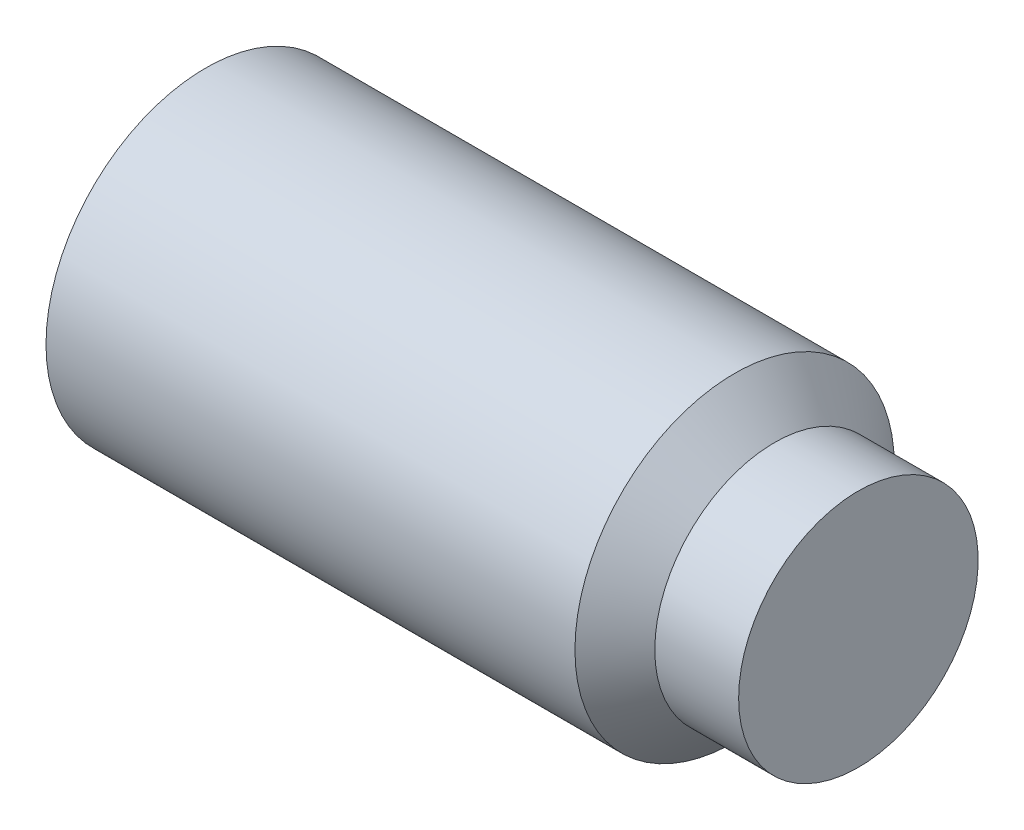
SolidWorks part; units mm, degrees
revolve "BaseBody" add sketch "BodySke" angle 360 about L5
sketch "BodySke" plane through (0, 0, 0) normal (0, 0, 1) x (1, 0, 0)
  line L0 (0, 0) -> (0, 10.352)
  line L1 (0, 10.352) -> (0.9515, 12)
  line L2 (0.9515, 12) -> (40.7, 12)
  line L3 (40.7, 12) -> (43.7, 9)
  line L4 (50, 0) -> (0, 0)
  line L5 (-12.7, 0) -> (88.9, 0) construction
  line L6 (43.7, 9) -> (50, 9)
  line L7 (50, 9) -> (50, 0)
  line L8 (0, -10.352) -> (0.9515, -12) construction
  line L9 (43.7, -9) -> (50, -9) construction
  line L10 (1.5, 15.875) -> (1.5, -3.175) construction
  dimension "Diameter" = 24
  dimension "Drive_ch_ang" = 60
  dimension "Minor_dia" = 20.704
  dimension "Dog_dia" = 18
  dimension "Dog_len" = 6.3
  dimension "Length" = 50
  dimension "D1" = 45
  dimension "Advance" = 3
cosmetic thread "ThreadCosmetic" [suppressed] parameters "Thread_minor"=20.704
ref_plane "Plane1" through (0, 0, 0) normal (0, 0, 1) x (1, 0, 0)
ref_plane "Plane2" through (0, 0, 0) normal (0, 1, 0) x (1, 0, 0)
ref_plane "Plane3" through (0, 0, 0) normal (1, 0, 0) x (0, 0, -1)
sketch "Sketch2" plane through (0, 0, 0) normal (-1, 0, 0) x (0, 0, 1)
  line L0 (3.4641, 6) -> (-3.4641, 6)
  line L1 (-3.4641, 6) -> (-6.9282, 0)
  line L2 (3.4641, 6) -> (6.9282, 0)
  line L3 (3.4641, -6) -> (6.9282, 0)
  line L4 (3.4641, -6) -> (-3.4641, -6)
  line L5 (-3.4641, -6) -> (-6.9282, 0)
  dimension "Hex_size" = 12
  dimension "D2" = 6
  dimension "D3" = 6
extrude "Hex" cut sketch "Sketch2" against normal blind 15
sketch "ThdSchSke" plane through (0, 0, 0) normal (0, 0, 1) x (1, 0, 0)
  line L0 (0.9515, -10.352) -> (-0.2025, -12)
  line L1 (0.9515, -10.352) -> (2.1054, -12)
  line L2 (2.1054, -12) -> (2.1054, -15)
  line L3 (-3.175, 0) -> (5.1513, 0) construction
  line L4 (0.9515, 12) -> (0.9515, -12) construction
  line L5 (2.1054, -15) -> (-0.2025, -15)
  line L6 (-0.2025, -15) -> (-0.2025, -12)
  dimension "Thread_minor" = 20.704
  dimension "Diameter" = 24
revolve "ThreadSchematic" [suppressed] cut sketch "ThdSchSke" angle 360 about L3
pattern_linear "ThdSchPat" [suppressed]
equation "\"D2@Sketch2\" = \"Hex_size@Sketch2\" / 2"
equation "\"D3@Sketch2\" = \"Hex_size@Sketch2\" / 2"
equation "\"Thread_minor@ThreadCosmetic\" = \"Minor_dia@BodySke\""
equation "\"Thread_minor@ThdSchSke\" = \"Thread_minor@ThreadCosmetic\""
equation "\"Diameter@ThdSchSke\" = \"Diameter@BodySke\""
equation "\"Overcut@ThdSchSke\" = \"Diameter@BodySke\" * 1.25"
equation "\"Num_threads@ThdSchPat\" = int( (\"Length@BodySke\" - ( ( ( \"Diameter@BodySke\" - \"Minor_dia@BodySke\" ) * 0.5 ) / tan( \"Drive_ch_ang@BodySke\" * 0.017453292 ) ) - \"Dog_len@BodySke\" ) / \"Advance@BodySke\" + 0.999 )  + 1"
equation "\"Advance@ThdSchPat\" = (\"Length@BodySke\" - ( ( ( \"Diameter@BodySke\" - \"Minor_dia@BodySke\" ) * 0.5 ) / tan( \"Drive_ch_ang@BodySke\" * 0.017453292 ) ) - \"Dog_len@BodySke\" ) /  (\"Num_threads@ThdSchPat\" - 1) 'relax it"
equation "\"Num_threads@ThdSchPat\" = \"Num_threads@ThdSchPat\" - sgn( \"Num_threads@ThdSchPat\" - 1) '---chamfered tips only---"
